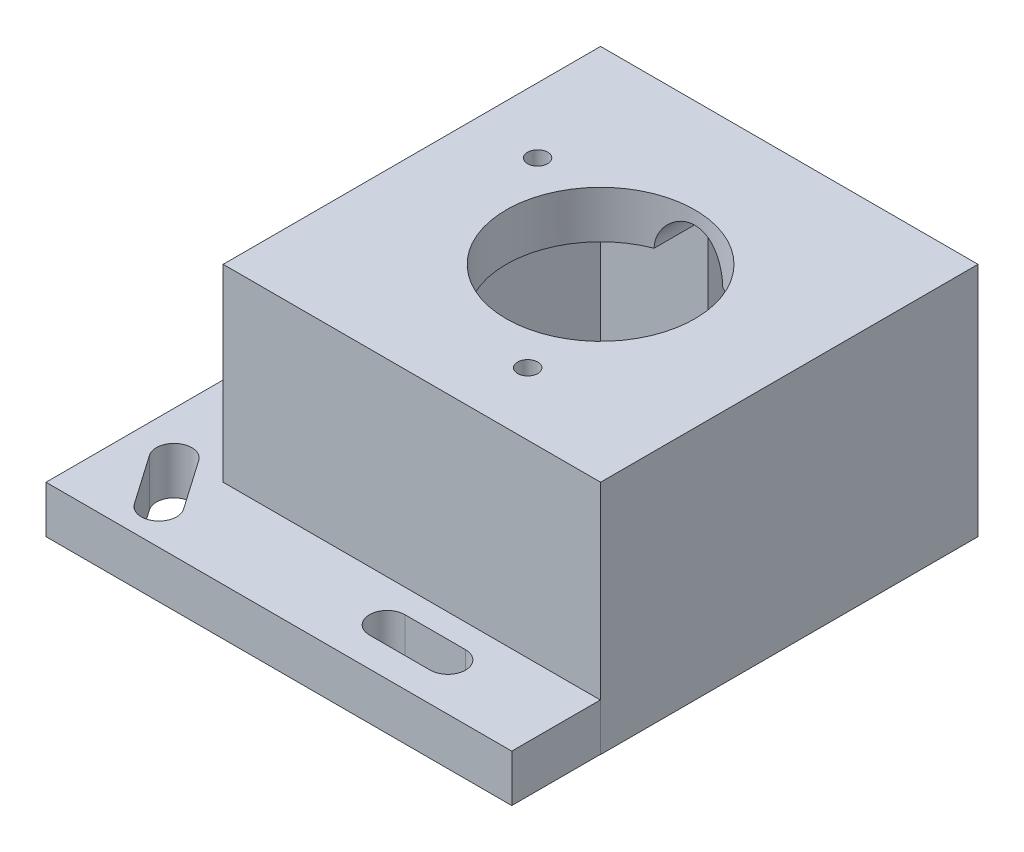
SolidWorks part; units mm, degrees
ref_plane "Front Plane" through (0, 0, 0) normal (0, 0, 1) x (1, 0, 0)
ref_plane "Top Plane" through (0, 0, 0) normal (0, 1, 0) x (1, 0, 0)
ref_plane "Right Plane" through (0, 0, 0) normal (1, 0, 0) x (0, 0, -1)
sketch "Sketch1" plane through (0, 0, 0) normal (0, 1, 0) x (1, 0, 0)
  line L1 (-25.4, 25.4) -> (25.4, 25.4)
  line L2 (-25.4, 25.4) -> (-25.4, -25.4)
  line L3 (-25.4, -25.4) -> (25.4, -25.4)
  line L4 (25.4, 25.4) -> (25.4, -25.4)
  line L5 (-25.4, 25.4) -> (25.4, -25.4) construction
  line L6 (-25.4, -25.4) -> (25.4, 25.4) construction
  circle A0 centre (0, 0) radius 12.7
  point P0 (0, 0)
extrude "Boss-Extrude2" add sketch "Sketch1" along normal blind 31.75
sketch "Sketch4" plane through (0, 0, 0) normal (0, -1, 0) x (-1, 0, 0)
  line L1 (25.4, -25.4) -> (-25.3664, -25.4)
  line L2 (37.3213, -25.4) -> (37.3213, -37.3213)
  line L3 (37.3213, -37.3213) -> (-25.3664, -37.3213)
  line L4 (-25.3664, -25.4) -> (-25.3664, -37.3213)
  line L6 (25.4, -25.4) -> (25.4, 25.4)
  line L7 (25.4, 25.4) -> (37.3213, 25.4)
  line L8 (37.3213, -25.4) -> (37.3213, 25.4)
  point P1 (0, 0)
extrude "Boss-Extrude5" add sketch "Sketch4" against normal blind 6.35
sketch "Sketch10" plane through (0, 6.35, 0) normal (0, 1, 0) x (1, 0, 0)
  line L0 (10.4341, -30.988) -> (2.2659, -30.988) construction
  line L1 (10.4341, -33.3693) -> (2.2659, -33.3693)
  line L2 (10.4341, -28.6067) -> (2.2659, -28.6067)
  arc A0 (10.4341, -33.3693) -> (10.4341, -28.6067) centre (10.4341, -30.988) ccw
  arc A1 (2.2659, -28.6067) -> (2.2659, -33.3693) centre (2.2659, -30.988) ccw
  point P1 (6.35, -30.988)
sketch "Sketch11" plane through (0, 6.35, 0) normal (0, 1, 0) x (1, 0, 0)
  line L0 (-30.988, 10.4341) -> (-30.988, 2.2659) construction
  line L1 (-28.6067, 10.4341) -> (-28.6067, 2.2659)
  line L2 (-33.3693, 10.4341) -> (-33.3693, 2.2659)
  line L3 (-31.5425, -25.8575) -> (-26.8775, -32.5625) construction
  line L4 (-29.5879, -24.4975) -> (-24.9228, -31.2025)
  line L5 (-33.4972, -27.2175) -> (-28.8321, -33.9225)
  arc A0 (-28.6067, 10.4341) -> (-33.3693, 10.4341) centre (-30.988, 10.4341) ccw
  arc A1 (-33.3693, 2.2659) -> (-28.6067, 2.2659) centre (-30.988, 2.2659) ccw
  arc A2 (-29.5879, -24.4975) -> (-33.4972, -27.2175) centre (-31.5425, -25.8575) ccw
  arc A3 (-28.8321, -33.9225) -> (-24.9228, -31.2025) centre (-26.8775, -32.5625) ccw
  point P4 (-29.21, -29.21)
  point P7 (-30.988, 6.35)
extrude "Cut-Extrude2" cut sketch "Sketch11" against normal blind 6.35
extrude "Cut-Extrude3" cut sketch "Sketch10" against normal blind 6.35
sketch "Sketch12" plane through (0, 0, 0) normal (0, -1, 0) x (-1, 0, 0)
  line L1 (19.05, -19.05) -> (-19.05, -19.05)
  line L2 (19.05, -19.05) -> (19.05, 19.05)
  line L3 (19.05, 19.05) -> (-19.05, 19.05)
  line L4 (-19.05, -19.05) -> (-19.05, 19.05)
extrude "Cut-Extrude6" cut sketch "Sketch12" against normal blind 25.4
hole_wizard "#6-32 Tapped Hole3" positions "3DSketch4" profile "Sketch15" tap size "#6-32" standard "ANSI Inch" end condition through all
sketch3d "3DSketch4"
  point P0 (7.1581, 31.75, 16.9671)
  point P2 (-16.6335, 31.75, -8.1587)
sketch "Sketch15" plane through (7.1581, 31.75, 16.9671) normal (1, 0, 0) x (0, 0, 1)
  line L0 (0, 0) -> (0, 31.75)
  line L1 (0, 31.75) -> (1.3525, 31.75)
  line L2 (1.3525, 31.75) -> (1.3525, 0)
  line L5 (1.3525, 0) -> (0, 0)
  line L11 (0, -6.35) -> (0, 107.95) construction
  dimension "Thru Tap Drill Dia." = 2.7051
  dimension "Thru Tap Drill Depth" = 31.75
cosmetic thread "Hole Thread5" parameters "D2"=3.5052
cosmetic thread "Hole Thread6" parameters "D2"=3.5052
sketch "Sketch18" plane through (0, 0, -25.4) normal (0, 0, -1) x (-1, 0, 0)
  line L0 (0, 25.3343) -> (0, 9.2097) construction
  line L2 (4.6204, 25.3343) -> (4.6204, 9.2097)
  line L3 (-4.6204, 25.3343) -> (-4.6204, 9.2097)
  arc A0 (4.6204, 25.3343) -> (-4.6204, 25.3343) centre (0, 25.3343) ccw
  arc A1 (-4.6204, 9.2097) -> (4.6204, 9.2097) centre (0, 9.2097) ccw
  point P2 (0, 0)
  point P3 (0, 0)
  point P5 (0, 17.272)
  point P10 (0, 0)
  point P11 (0, 0)
  point P12 (0, 0)
  point P13 (0, 0)
  point P14 (0, 0)
  point P15 (0, 0)
extrude "Cut-Extrude7" cut sketch "Sketch18" against normal blind 25.4
